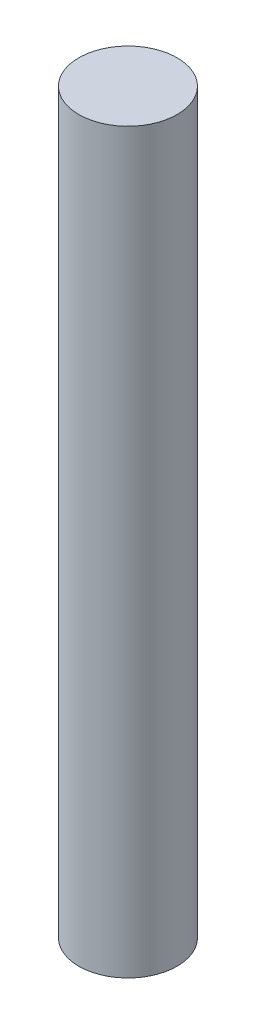
SolidWorks part; units mm, degrees
material "Copper"
ref_plane "Front Plane" through (0, 0, 0) normal (0, 0, 1) x (1, 0, 0)
ref_plane "Top Plane" through (0, 0, 0) normal (0, 1, 0) x (1, 0, 0)
ref_plane "Right Plane" through (0, 0, 0) normal (1, 0, 0) x (0, 0, -1)
sketch "Sketch2" plane through (0, 0, 0) normal (0, 1, 0) x (1, 0, 0)
  circle A0 centre (0, 0) radius 2
  dimension "D1" = 4
extrude "Boss-Extrude1" add sketch "Sketch2" along normal blind 30
equation "\"t\"= 30"
equation "\"D1@Boss-Extrude1\"= \"t\""
